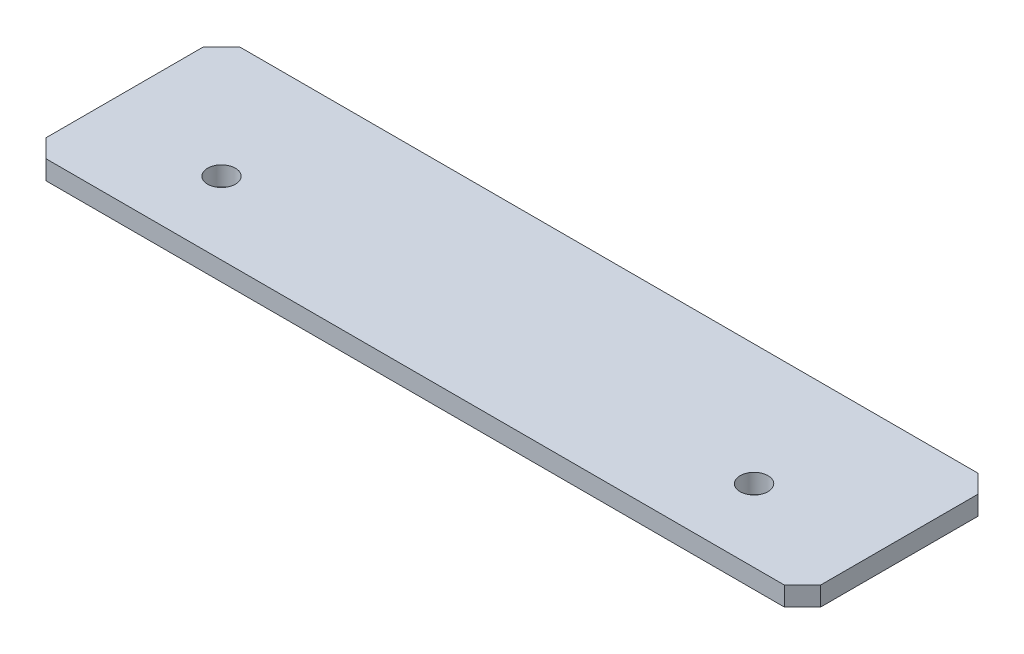
SolidWorks part; units mm, degrees
ref_plane "Front Plane" through (0, 0, 0) normal (0, 0, 1) x (1, 0, 0)
ref_plane "Top Plane" through (0, 0, 0) normal (0, 1, 0) x (1, 0, 0)
ref_plane "Right Plane" through (0, 0, 0) normal (1, 0, 0) x (0, 0, -1)
sketch "Sketch1" plane through (0, 0, 0) normal (0, 1, 0) x (1, 0, 0)
  line L0 (-320, 65) -> (-305, 80)
  line L1 (-305, 80) -> (305, 80)
  line L2 (-320, 65) -> (-320, -65)
  line L3 (-305, -80) -> (305, -80)
  line L4 (320, 65) -> (320, -65)
  line L5 (-320, 80) -> (320, -80) construction
  line L6 (-320, -80) -> (320, 80) construction
  line L7 (305, 80) -> (320, 65)
  line L8 (-320, -65) -> (-305, -80)
  line L9 (305, -80) -> (320, -65)
  line L13 (0, 225.5488) -> (0, -265.5356) construction
  circle A6 centre (-220, -20) radius 11.5
  circle A7 centre (220, -20) radius 11.5
  point P0 (0, 0)
  dimension "D14" = 60
  dimension "D11" = 23
  dimension "D12" = 23
  dimension "D1" = 160
  dimension "D2" = 640
  dimension "D3" = 15
  dimension "D4" = 45
  dimension "D5" = 15
  dimension "D6" = 45
  dimension "D7" = 15
  dimension "D8" = 45
  dimension "D9" = 15
  dimension "D10" = 45
  dimension "D13" = 100
  dimension "D15" = 60
  dimension "D16" = 100
extrude "Boss-Extrude1" add sketch "Sketch1" along normal mid plane 15.8
